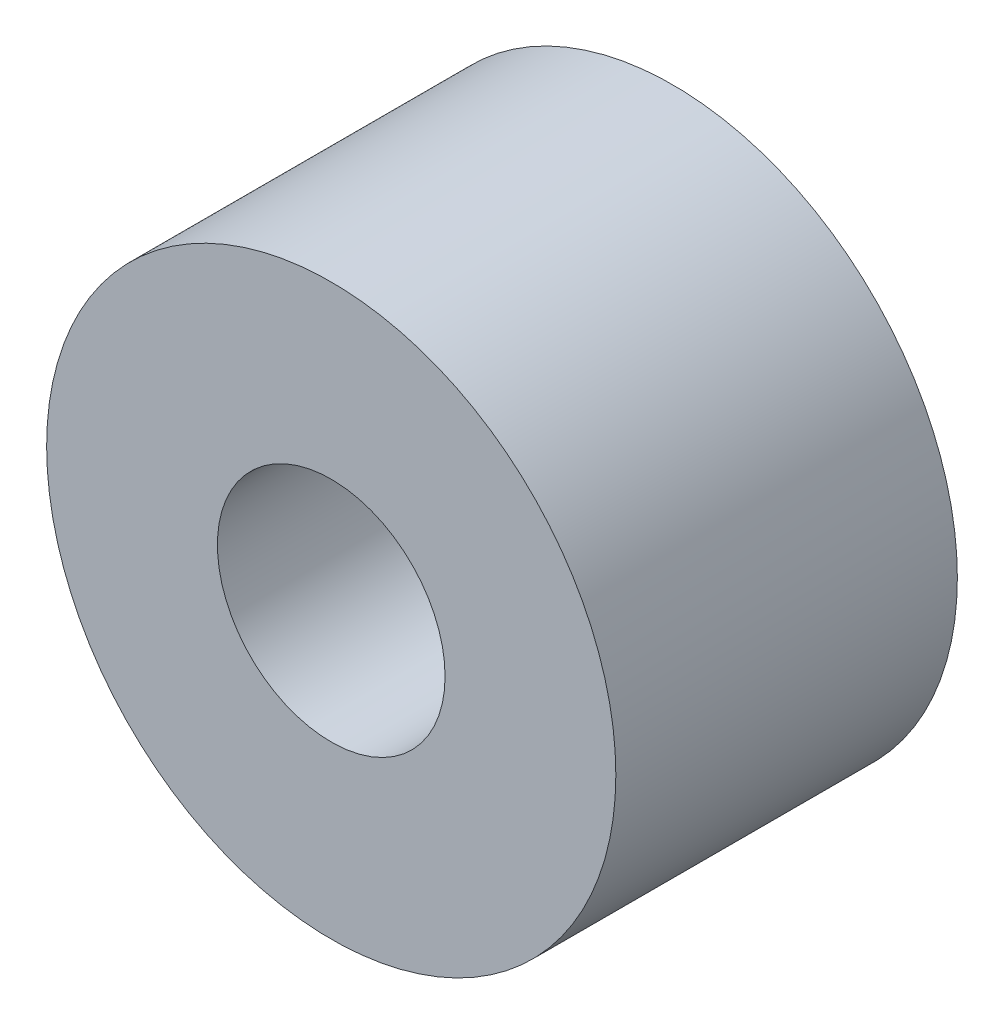
SolidWorks part; units mm, degrees
ref_plane "Front Plane" through (0, 0, 0) normal (0, 0, 1) x (1, 0, 0)
ref_plane "Top Plane" through (0, 0, 0) normal (0, 1, 0) x (1, 0, 0)
ref_plane "Right Plane" through (0, 0, 0) normal (1, 0, 0) x (0, 0, -1)
sketch "Sketch1" plane through (0, 0, 0) normal (0, 0, 1) x (1, 0, 0)
  circle A0 centre (0, 0) radius 5
extrude "Boss-Extrude1" add sketch "Sketch1" along normal blind 6
sketch "Sketch2" plane through (0, 0, 6) normal (0, 0, 1) x (1, 0, 0)
  circle A0 centre (0, 0) radius 2
extrude "Cut-Extrude1" cut sketch "Sketch2" against normal blind 6
